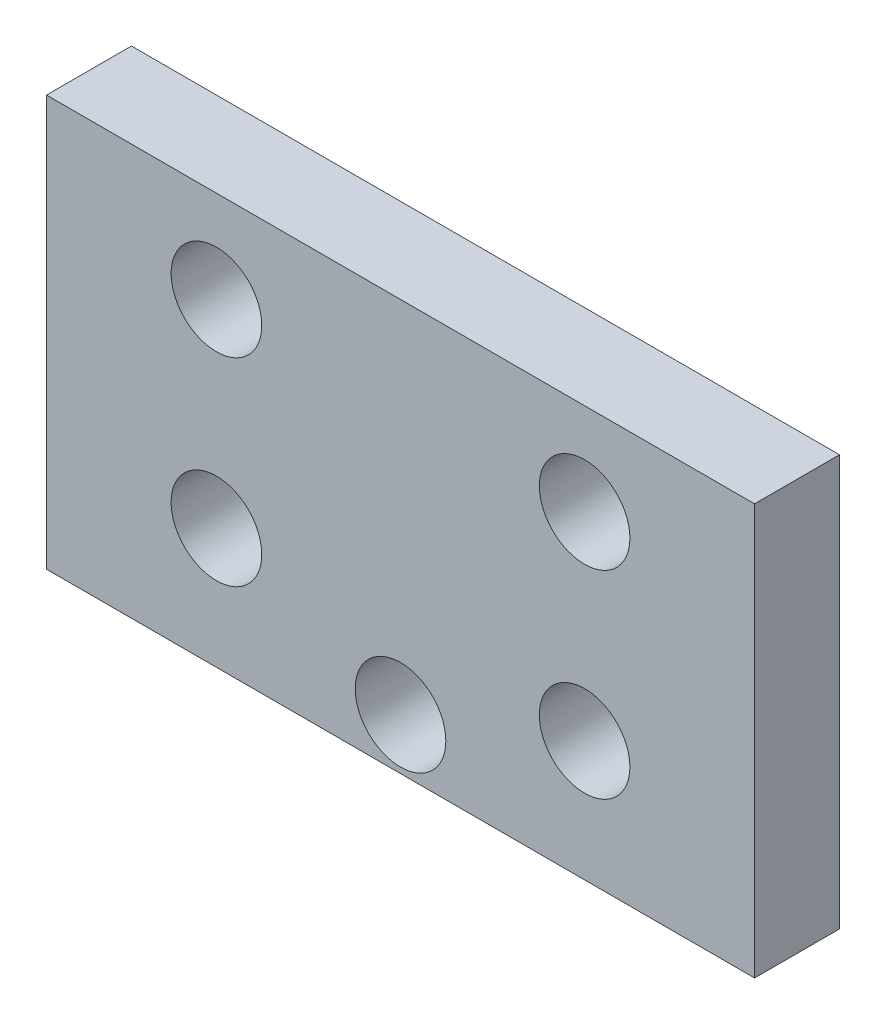
SolidWorks part; units mm, degrees
ref_plane "前视基准面" through (0, 0, 0) normal (0, 0, 1) x (1, 0, 0)
ref_plane "上视基准面" through (0, 0, 0) normal (0, 1, 0) x (1, 0, 0)
ref_plane "右视基准面" through (0, 0, 0) normal (1, 0, 0) x (0, 0, -1)
sketch "草图1" plane through (0, 0, 0) normal (0, 0, 1) x (1, 0, 0)
  line L1 (12.5, -7.25) -> (-12.5, -7.25)
  line L2 (12.5, -7.25) -> (12.5, 7.25)
  line L3 (12.5, 7.25) -> (-12.5, 7.25)
  line L4 (-12.5, -7.25) -> (-12.5, 7.25)
  line L5 (12.5, -7.25) -> (-12.5, 7.25) construction
  line L6 (12.5, 7.25) -> (-12.5, -7.25) construction
  line L7 (6.5, -3) -> (-6.5, -3) construction
  line L8 (6.5, -3) -> (6.5, 4) construction
  line L9 (6.5, 4) -> (-6.5, 4) construction
  line L10 (-6.5, -3) -> (-6.5, 4) construction
  line L11 (6.5, -3) -> (-6.5, 4) construction
  line L12 (6.5, 4) -> (-6.5, -3) construction
  circle A0 centre (-6.5, 4) radius 1.6
  circle A1 centre (6.5, 4) radius 1.6
  circle A2 centre (6.5, -3) radius 1.6
  circle A3 centre (0, -5.45) radius 1.6
  circle A4 centre (-6.5, -3) radius 1.6
  point P0 (0, 0)
  point P6 (0, 0.5)
  dimension "D5" = 3.2
  dimension "D1" = 7
  dimension "D2" = 13
  dimension "D3" = 25
  dimension "D4" = 14.5
  dimension "D6" = 1.8
  dimension "D7" = 4.25
extrude "凸台-拉伸1" add sketch "草图1" along normal blind 3
